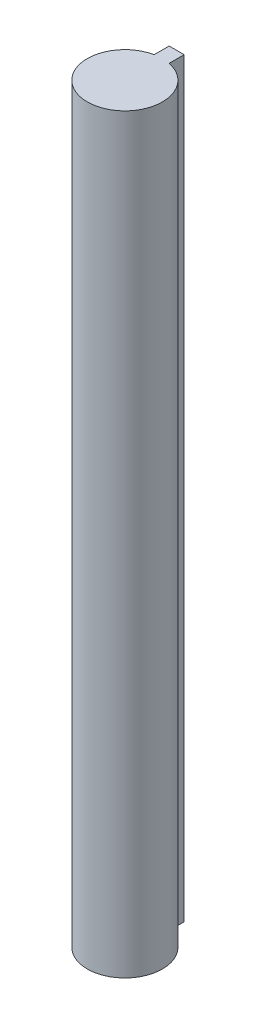
SolidWorks part; units mm, degrees
ref_plane "前视基准面" through (0, 0, 0) normal (0, 0, 1) x (1, 0, 0)
ref_plane "上视基准面" through (0, 0, 0) normal (0, 1, 0) x (1, 0, 0)
ref_plane "右视基准面" through (0, 0, 0) normal (1, 0, 0) x (0, 0, -1)
sketch "草图1" plane through (0, 0, 0) normal (0, 1, 0) x (1, 0, 0)
  line L1 (0, -6.6512) -> (0, 18.474) construction
  line L2 (-2, 9.798) -> (-2, 13.798)
  line L3 (-2, 13.798) -> (2, 13.798)
  line L4 (2, 9.798) -> (2, 13.798)
  arc A0 (-2, 9.798) -> (2, 9.798) centre (0, 0) ccw
  point P10 (0, 13.798)
  dimension "D1" = 4
  dimension "D3" = 10
  dimension "D2" = 4
extrude "凸台-拉伸1" add sketch "草图1" along normal blind 200
